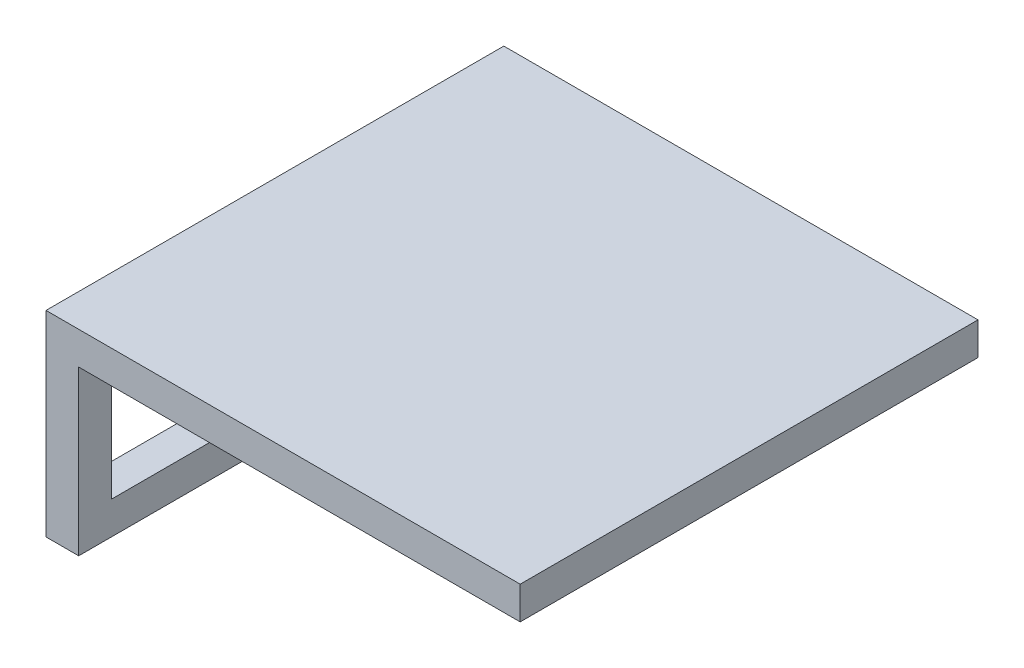
SolidWorks part; units mm, degrees
material "ABS PC"
ref_plane "Front Plane" through (0, 0, 0) normal (0, 0, 1) x (1, 0, 0)
ref_plane "Top Plane" through (0, 0, 0) normal (0, 1, 0) x (1, 0, 0)
ref_plane "Right Plane" through (0, 0, 0) normal (1, 0, 0) x (0, 0, -1)
sketch "Sketch1" plane through (0, 0, 0) normal (0, 0, 1) x (1, 0, 0)
  line L0 (67.5, 0) -> (67.5, -2) construction
  line L1 (0, 0) -> (-5, 0)
  line L2 (0, 0) -> (0, 30)
  line L3 (0, 30) -> (-5, 30)
  line L4 (-5, 0) -> (-5, 30)
  line L5 (0, 30) -> (67.5, 30)
  line L6 (0, 30) -> (0, 25)
  line L7 (0, 25) -> (67.5, 25)
  line L8 (67.5, 30) -> (67.5, 25)
  dimension "D1" = 5
  dimension "D2" = 30
  dimension "D4" = 5
extrude "Boss-Extrude1" add sketch "Sketch1" along normal mid plane 70 contours L4 L1 L2 L3 | L8 L5 L2 L7
sketch "Sketch2" plane through (0, 0, 0) normal (0, -1, 0) x (1, 0, 0)
  line L0 (-2.5, 10) -> (-2.5, -10) construction
  line L1 (-5, 0) -> (0, 0)
  line L2 (-5, 35) -> (-5, -35) construction
  circle A0 centre (-2.5, 10) radius 1
  circle A1 centre (-2.5, -10) radius 1
  point P9 (-2.5, 0)
  dimension "D1" = 2
  dimension "D2" = 2
  dimension "D3" = 20
extrude "Cut-Extrude1" cut sketch "Sketch2" against normal blind 10 contours A1 | A0
sketch "Sketch3" plane through (-5, 0, 0) normal (-1, 0, 0) x (0, 0, 1)
  line L0 (35, 0) -> (35, 30) construction
  line L1 (-30, 25) -> (30, 25)
  line L2 (-30, 25) -> (-30, 5)
  line L3 (-30, 5) -> (30, 5)
  line L4 (30, 25) -> (30, 5)
  line L5 (35, 0) -> (-35, 0) construction
  dimension "D1" = 20
  dimension "D2" = 60
  dimension "D3" = 5
  dimension "D4" = 5
extrude "Cut-Extrude2" cut sketch "Sketch3" against normal blind 10
